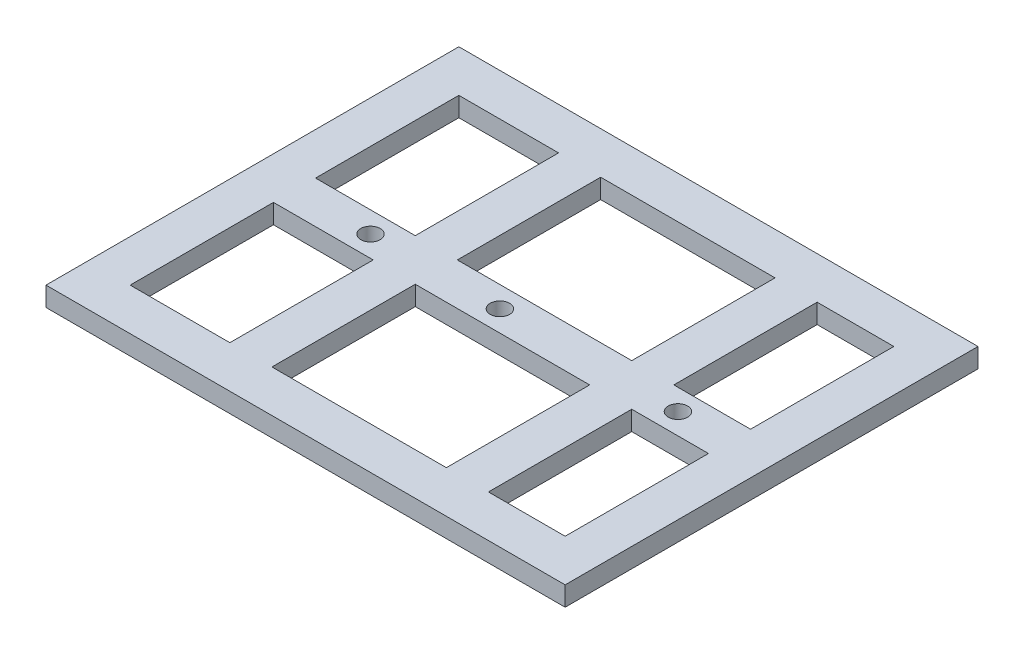
SolidWorks part; units mm, degrees
ref_plane "Front Plane" through (0, 0, 0) normal (0, 0, 1) x (1, 0, 0)
ref_plane "Top Plane" through (0, 0, 0) normal (0, 1, 0) x (1, 0, 0)
ref_plane "Right Plane" through (0, 0, 0) normal (1, 0, 0) x (0, 0, -1)
sketch "Sketch1" plane through (0, 0, 0) normal (0, 1, 0) x (1, 0, 0)
  line L21 (-40.1013, -31.8905) -> (-40.1013, 31.8905)
  line L25 (-33.6013, -25.3905) -> (-18.1956, -25.3905)
  line L26 (-33.6013, -25.3905) -> (-33.6013, -3.25)
  line L27 (-33.6013, 25.3905) -> (-18.1956, 25.3905)
  line L28 (33.6013, -25.3905) -> (33.6013, -3.25)
  line L29 (-33.6013, -25.3905) -> (33.6013, 25.3905) construction
  line L30 (-33.6013, 25.3905) -> (33.6013, -25.3905) construction
  line L31 (-40.1013, 31.8905) -> (40.1013, 31.8905)
  line L32 (40.1013, -31.8905) -> (40.1013, 31.8905)
  line L33 (-40.1013, -31.8905) -> (40.1013, -31.8905)
  line L34 (-18.1956, 25.3905) -> (-18.1956, 3.25)
  line L35 (-11.6956, 25.3905) -> (-11.6956, 3.25)
  line L36 (15.2482, 25.3905) -> (15.2482, 3.25)
  line L37 (21.7482, 25.3905) -> (21.7482, 3.25)
  line L38 (-33.6013, 3.25) -> (-18.1956, 3.25)
  line L39 (-33.6013, -3.25) -> (-18.1956, -3.25)
  line L40 (-18.1956, -3.25) -> (-18.1956, -25.3905)
  line L41 (-11.6956, -3.25) -> (-11.6956, -25.3905)
  line L42 (-11.6956, 3.25) -> (15.2482, 3.25)
  line L43 (-11.6956, -3.25) -> (15.2482, -3.25)
  line L44 (21.7482, -3.25) -> (33.6013, -3.25)
  line L45 (21.7482, 3.25) -> (33.6013, 3.25)
  line L46 (15.2482, -3.25) -> (15.2482, -25.3905)
  line L47 (21.7482, -3.25) -> (21.7482, -25.3905)
  line L48 (33.6013, 0) -> (-33.6013, 0) construction
  line L49 (-11.6956, 25.3905) -> (15.2482, 25.3905)
  line L50 (-33.6013, 25.3905) -> (33.6013, 25.3905) construction
  line L51 (21.7482, 25.3905) -> (33.6013, 25.3905)
  line L52 (33.6013, 3.25) -> (33.6013, 25.3905)
  line L53 (33.6013, -25.3905) -> (33.6013, 25.3905) construction
  line L54 (-33.6013, 3.25) -> (-33.6013, 25.3905)
  line L55 (-33.6013, -25.3905) -> (-33.6013, 25.3905) construction
  line L56 (-11.6956, -25.3905) -> (15.2482, -25.3905)
  line L57 (-33.6013, -25.3905) -> (33.6013, -25.3905) construction
  line L58 (21.7482, -25.3905) -> (33.6013, -25.3905)
  circle A0 centre (-21.864, 0) radius 1.5
  circle A1 centre (-1.864, 0) radius 1.5
  circle A2 centre (25.636, 0) radius 1.5
  point P0 (0, 0)
  point P38 (13.4231, 0)
  dimension "D5" = 3
  dimension "D1" = 6.5
  dimension "D2" = 6.5
  dimension "D3" = 6.5
  dimension "D4" = 6.5
  dimension "D6" = 20
  dimension "D7" = 27.5
extrude "Boss-Extrude1" add sketch "Sketch1" along normal mid plane 3
